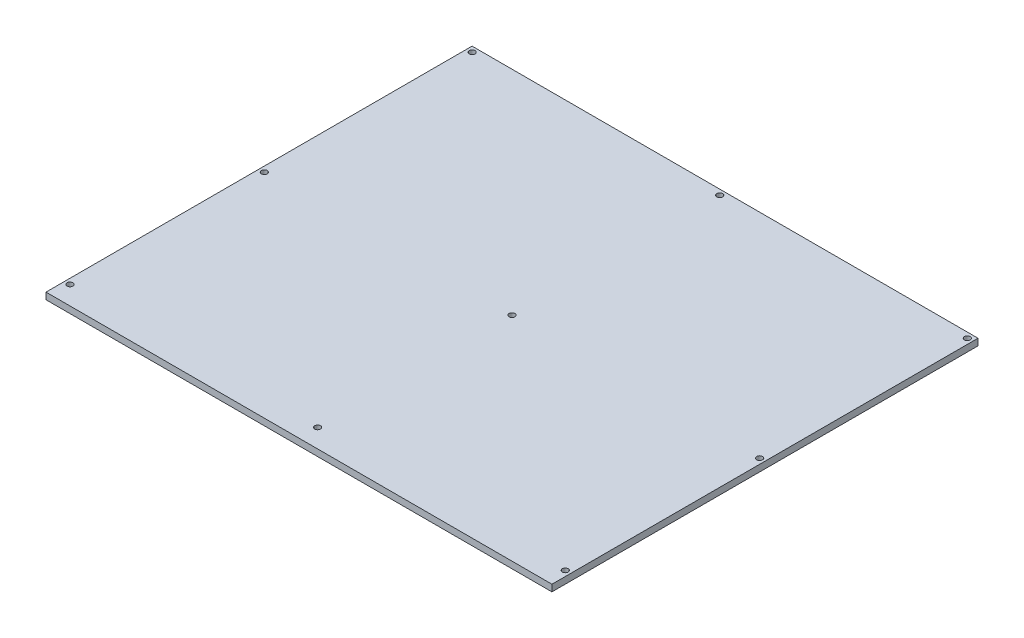
SolidWorks part; units mm, degrees
ref_plane "Front Plane" through (0, 0, 0) normal (0, 0, 1) x (1, 0, 0)
ref_plane "Top Plane" through (0, 0, 0) normal (0, 1, 0) x (1, 0, 0)
ref_plane "Right Plane" through (0, 0, 0) normal (1, 0, 0) x (0, 0, -1)
sketch "Sketch1" plane through (0, 0, 0) normal (0, 1, 0) x (1, 0, 0)
  line L1 (0, 0) -> (380, 0)
  line L2 (0, 0) -> (0, 320)
  line L3 (0, 320) -> (380, 320)
  line L4 (380, 0) -> (380, 320)
  dimension "D1" = 380
  dimension "D2" = 320
extrude "Boss-Extrude1" add sketch "Sketch1" along normal blind 5
sketch "Sketch2" plane through (0, 5, 0) normal (0, 1, 0) x (1, 0, 0)
  line L0 (190, 320) -> (190, 0) construction
  line L1 (380, 320) -> (0, 320) construction
  line L2 (0, 0) -> (380, 0) construction
  line L3 (0, 160) -> (190, 160) construction
  line L4 (0, 320) -> (0, 0) construction
  line L5 (190, 160) -> (380, 160) construction
  line L6 (380, 0) -> (380, 320) construction
  line L7 (4, 316) -> (190, 316) construction
  line L8 (4, 14) -> (190, 14) construction
  circle A0 centre (4, 316) radius 2.2
  circle A1 centre (4, 160) radius 2.2
  circle A2 centre (4, 14) radius 2.2
  circle A3 centre (376, 160) radius 2.2
  circle A4 centre (376, 14) radius 2.2
  circle A5 centre (376, 316) radius 2.2
  circle A6 centre (190, 160) radius 2.2
  circle A7 centre (190, 14) radius 2.2
  circle A8 centre (190, 316) radius 2.2
  dimension "D1" = 4.4
  dimension "D2" = 4.4
  dimension "D3" = 4.4
  dimension "D4" = 14
  dimension "D5" = 4
  dimension "D6" = 4
  dimension "D7" = 4.4
  dimension "D8" = 4.4
  dimension "D9" = 4.4
extrude "Cut-Extrude1" cut sketch "Sketch2" against normal blind 5
